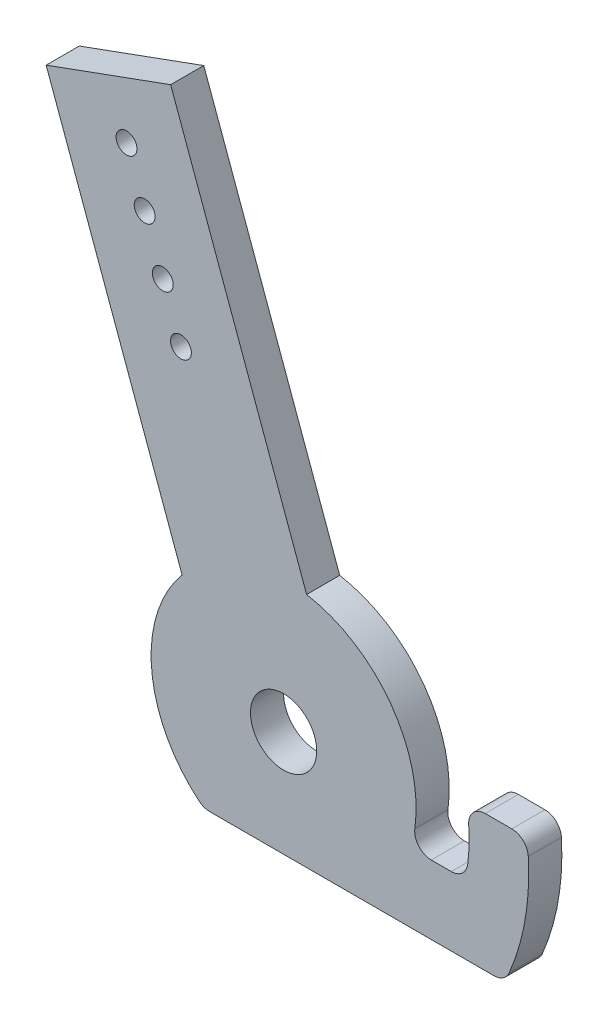
SolidWorks part; units mm, degrees
ref_plane "Front Plane" through (0, 0, 0) normal (0, 0, 1) x (1, 0, 0)
ref_plane "Top Plane" through (0, 0, 0) normal (0, 1, 0) x (1, 0, 0)
ref_plane "Right Plane" through (0, 0, 0) normal (1, 0, 0) x (0, 0, -1)
sketch "Sketch1" plane through (0, 0, 0) normal (0, 0, 1) x (1, 0, 0)
  line L0 (-11.3799, 21.9828) -> (-5.4128, 24.1547)
  line L1 (10.0803, -5.08) -> (-3.5355, -5.08)
  line L2 (8.0362, -1.778) -> (7.0756, -1.778)
  line L3 (-5.7901, 15.9083) -> (-4.9214, 13.5215) construction
  line L4 (0, 0) -> (16.6193, 0) construction
  line L6 (0, 0) -> (-11.2765, 30.982) construction
  line L7 (9.6619, 1.4436) -> (10.9345, 1.4436)
  line L8 (1.1027, 6.2535) -> (-5.4128, 24.1547)
  line L9 (-4.8644, 4.0817) -> (-11.3799, 21.9828)
  arc A0 (6.2894, -0.8749) -> (7.0756, -1.778) centre (7.0756, -0.9842) ccw
  arc A1 (8.0362, -1.778) -> (8.8241, -1.0807) centre (8.0362, -0.9842) ccw
  circle A2 centre (0, 0) radius 1.5875
  arc A3 (9.6619, 1.4436) -> (8.87, 0.5966) centre (9.6619, 0.6498) ccw
  arc A4 (10.8108, -4.5968) -> (11.7268, 0.6969) centre (0, 0) ccw
  arc A5 (8.8241, -1.0807) -> (8.87, 0.5966) centre (0, 0) ccw
  arc A6 (11.7268, 0.6969) -> (10.9345, 1.4436) centre (10.9345, 0.6498) ccw
  arc A7 (10.0803, -5.08) -> (10.8108, -4.5968) centre (10.0803, -4.2862) ccw
  circle A8 centre (-7.5276, 20.6819) radius 0.5
  circle A9 centre (-6.6589, 18.2951) radius 0.5
  circle A10 centre (-5.7901, 15.9083) radius 0.5
  arc A11 (-4.8644, 4.0817) -> (-4.0406, -4.8986) centre (0, 0) ccw
  arc A12 (6.2894, -0.8749) -> (1.1027, 6.2535) centre (0, 0) ccw
  circle A13 centre (-4.9214, 13.5215) radius 0.5
  arc A14 (-3.5355, -5.08) -> (-4.0406, -4.8986) centre (-3.5355, -4.2863) cw
extrude "Boss-Extrude1" add sketch "Sketch1" along normal blind 1.5875
